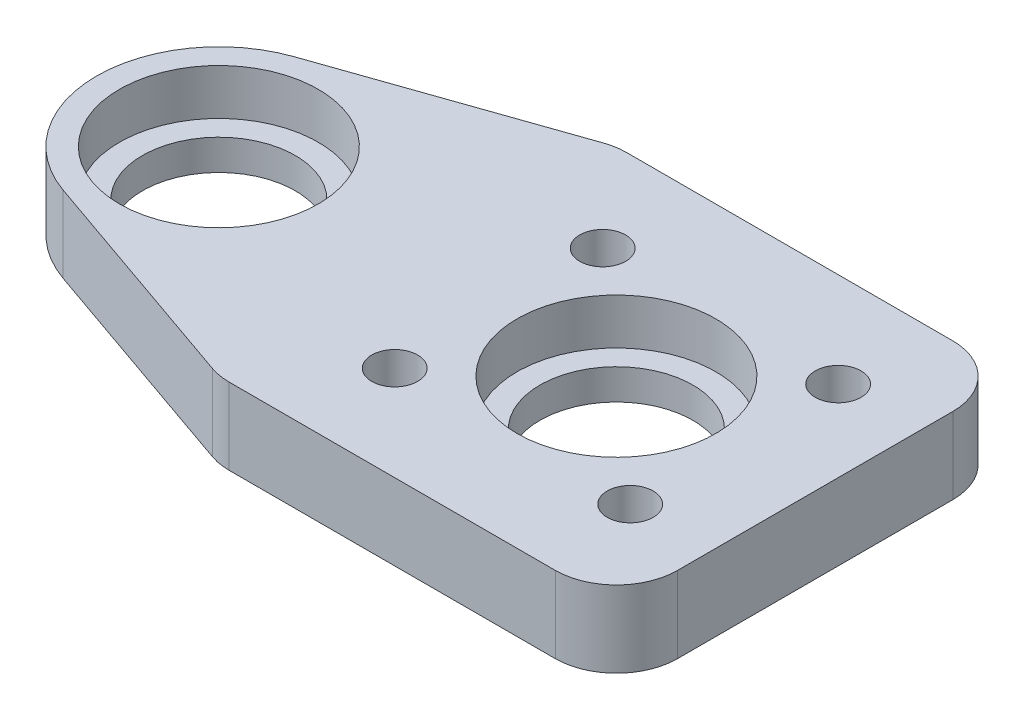
SolidWorks part; units mm, degrees
material "ABS"
ref_plane "Спереди" through (0, 0, 0) normal (0, 0, 1) x (1, 0, 0)
ref_plane "Сверху" through (0, 0, 0) normal (0, 1, 0) x (1, 0, 0)
ref_plane "Справа" through (0, 0, 0) normal (1, 0, 0) x (0, 0, -1)
sketch "Эскиз1" plane through (0, -185.8098, 0) normal (0, 1, 0) x (1, 0, 0)
  line L0 (-463.1111, 89.3029) -> (-450.1111, 89.3029) construction
  line L1 (-450.1111, 79.0029) -> (-450.1111, 113.0029) construction
  line L2 (-450.1111, 89.3029) -> (-450.1111, 76.3029)
  line L3 (-450.1111, 76.3029) -> (-476.1111, 76.3029)
  line L4 (-476.1111, 76.3029) -> (-476.1111, 102.3029) construction
  line L5 (-476.1111, 79.0029) -> (-476.1111, 113.0029) construction
  line L6 (-476.1111, 102.3029) -> (-450.1111, 102.3029)
  line L7 (-450.1111, 102.3029) -> (-450.1111, 89.3029)
  line L8 (-463.1111, 89.3029) -> (-489.1111, 89.3029) construction
  line L9 (-476.1111, 102.3029) -> (-491.7428, 96.8574)
  line L10 (-476.1111, 76.3029) -> (-491.7428, 81.7483)
  line L11 (-491.7428, 96.8574) -> (-491.7428, 81.7483) construction
  circle A0 centre (-470.8111, 96.1029) radius 1.5
  circle A1 centre (-455.4111, 96.1029) radius 1.5
  circle A2 centre (-455.4111, 82.5029) radius 1.5
  circle A3 centre (-470.8111, 82.5029) radius 1.5
  circle A4 centre (-463.1111, 89.3029) radius 5
  circle A5 centre (-489.1111, 89.3029) radius 5
  circle A6 centre (-489.1111, 89.3029) radius 7.9998 construction
  arc A7 (-491.7428, 81.7483) -> (-491.7428, 96.8574) centre (-489.1111, 89.3029) cw
  dimension "D1" = 3
  dimension "D2" = 3
  dimension "D3" = 3
  dimension "D4" = 3
  dimension "D5" = 10
  dimension "D9" = 26
  dimension "D10" = 10
  dimension "D11" = 15.9997
  dimension "D6" = 13
  dimension "D7" = 26
  dimension "D8" = 26
extrude "Бобышка-Вытянуть1" add sketch "Эскиз1" along normal blind 5
sketch "Эскиз2" plane through (0, -180.8098, 0) normal (0, 1, 0) x (1, 0, 0)
  circle A0 centre (-463.1111, 89.3029) radius 6.5
  circle A1 centre (-489.1111, 89.3029) radius 6.5
  dimension "D1" = 13
  dimension "D2" = 13
extrude "Вырез-Вытянуть1" cut sketch "Эскиз2" against normal blind 3
fillet "Скругление1" radius 4 4 edges at (-476.1111, -183.3098, -102.3029) (-450.1111, -183.3098, -102.3029) (-450.1111, -183.3098, -76.3029) (-476.1111, -183.3098, -76.3029)
